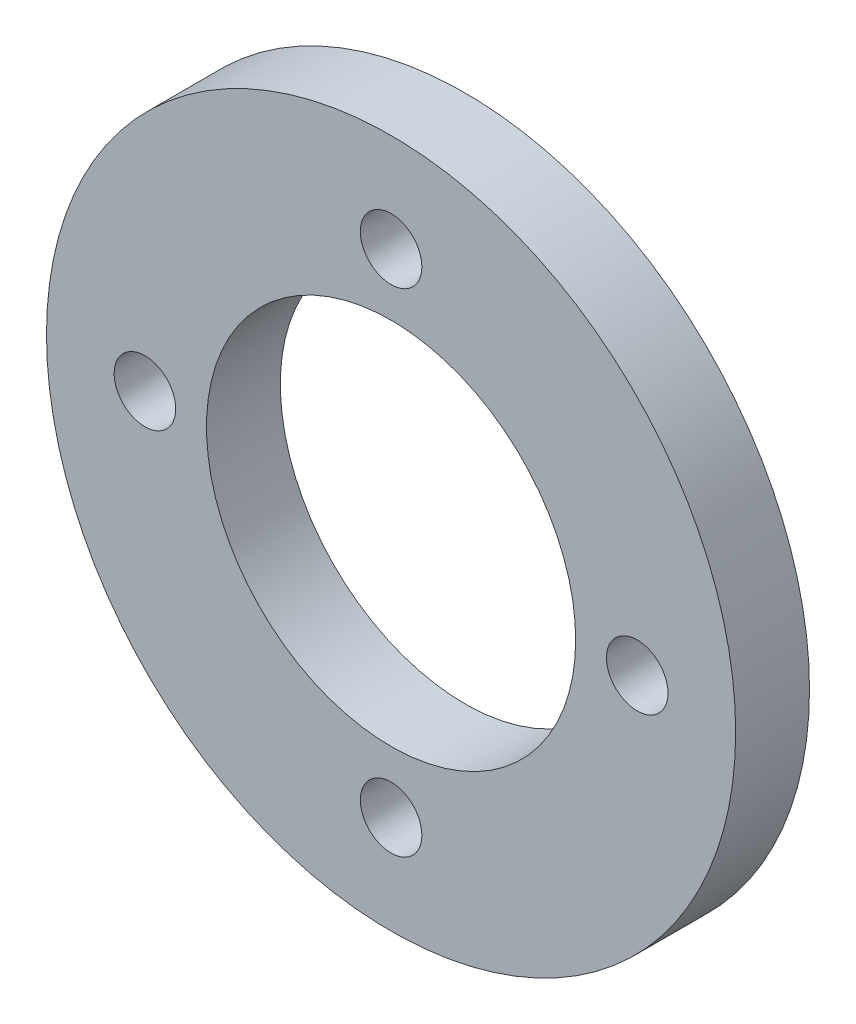
SolidWorks part; units mm, degrees
material "Thornel Mat VMA"
ref_plane "前视基准面" through (0, 0, 0) normal (0, 0, 1) x (1, 0, 0)
ref_plane "上视基准面" through (0, 0, 0) normal (0, 1, 0) x (1, 0, 0)
ref_plane "右视基准面" through (0, 0, 0) normal (1, 0, 0) x (0, 0, -1)
sketch "草图1" plane through (0, 0, 0) normal (0, 0, 1) x (1, 0, 0)
  circle A0 centre (0, 0) radius 12.5 construction
  circle A1 centre (0, 0) radius 14
  dimension "D1" = 25
  dimension "D2" = 1.5
extrude "凸台-拉伸1" add sketch "草图1" along normal blind 3
sketch "草图3" plane through (0, 0, 3) normal (0, 0, 1) x (1, 0, 0)
  circle A0 centre (10, 0) radius 1.025 construction
  circle A1 centre (0, -10) radius 1.025 construction
  circle A2 centre (-10, 0) radius 1.025 construction
  circle A3 centre (0, 10) radius 1.025 construction
  circle A4 centre (10, 0) radius 1.025 construction
  circle A5 centre (0, -10) radius 1.025 construction
  circle A6 centre (-10, 0) radius 1.025 construction
  circle A7 centre (0, 10) radius 1.025 construction
  circle A8 centre (10, 0) radius 1.25
  circle A9 centre (0, 10) radius 1.25
  circle A10 centre (-10, 0) radius 1.25
  circle A11 centre (0, -10) radius 1.25
  dimension "D1" = 2.5
extrude "切除-拉伸1" cut sketch "草图3" against normal blind 3
sketch "草图5" plane through (0, 0, 3) normal (0, 0, 1) x (1, 0, 0)
  line L0 (0, 0) -> (9.8995, 9.8995) construction
  line L1 (0, 14) -> (0, 0) construction
  line L2 (0, 0) -> (9.8995, -9.8995) construction
  circle A0 centre (0, 0) radius 14 construction
  dimension "D1" = 45
ref_plane "基准面1" through (0, 0, 0) normal (0.7071, 0.7071, 0) x (0.7071, -0.7071, 0)
ref_plane "基准面2" through (0, 0, 0) normal (0.7071, -0.7071, 0) x (0, 0, -1)
sketch "草图6" plane through (0, 0, 3) normal (0, 0, 1) x (1, 0, 0)
  line L0 (0, 0) -> (-26.8701, 26.8701) construction
  line L1 (-8.7447, -10.933) -> (-38.2382, 12.6572)
  line L2 (10.933, 8.7447) -> (-12.6572, 38.2382)
  line L3 (0, 0) -> (0, 14) construction
  circle A0 centre (-26.8701, 26.8701) radius 12.2
  arc A1 (-12.6572, 38.2382) -> (-38.2382, 12.6572) centre (-26.8701, 26.8701) ccw
  circle A2 centre (0, 0) radius 14 construction
  arc A3 (10.933, 8.7447) -> (-8.7447, -10.933) centre (0, 0) ccw
  circle A4 centre (-26.8701, 26.8701) radius 18.2 construction
  dimension "D1" = 24.4
  dimension "D2" = 38
  dimension "D4" = 45
  dimension "D3" = 6
extrude "凸台-拉伸2" [suppressed] add sketch "草图6" against normal up to surface (3 mm away)
sketch "草图7" plane through (0, 0, 3) normal (0, 0, 1) x (1, 0, 0)
  circle A0 centre (0, 0) radius 7.5
  dimension "D1" = 15
extrude "切除-拉伸2" cut sketch "草图7" against normal blind 10
